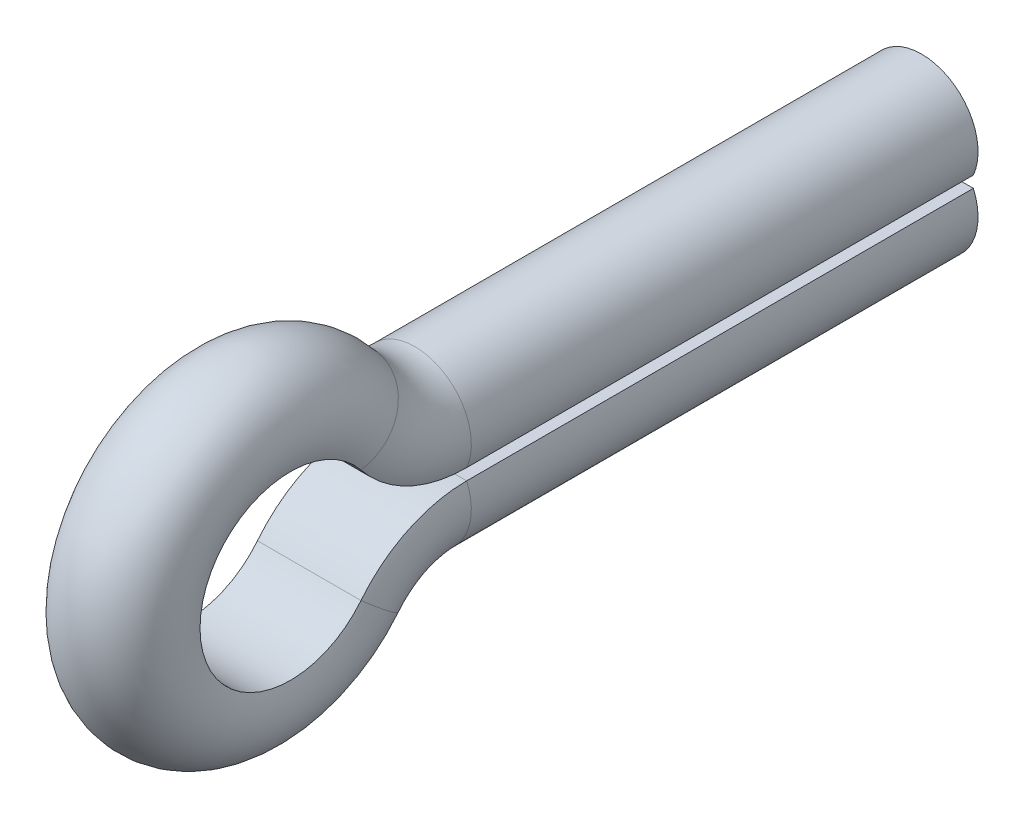
SolidWorks part; units mm, degrees
ref_plane "Front Plane" through (0, 0, 0) normal (0, 0, 1) x (1, 0, 0)
ref_plane "Top Plane" through (0, 0, 0) normal (0, 1, 0) x (1, 0, 0)
ref_plane "Right Plane" through (0, 0, 0) normal (1, 0, 0) x (0, 0, -1)
sketch "Sketch1" plane through (0, 0, 0) normal (1, 0, 0) x (0, 0, -1)
  line L0 (5, 0) -> (30.2482, 0) construction
  line L1 (7.8062, 1.25) -> (30.2482, 1.25)
  line L2 (7.8062, -1.25) -> (30.2482, -1.25)
  arc A0 (3.9031, 3.125) -> (3.9031, -3.125) centre (0, 0) ccw
  arc A1 (7.8062, -1.25) -> (3.9031, -3.125) centre (7.8062, -6.25) ccw
  arc A2 (3.9031, 3.125) -> (7.8062, 1.25) centre (7.8062, 6.25) ccw
  point P10 (4.8412, -1.25)
  point P13 (4.8412, 1.25)
  dimension "D1" = 10
  dimension "D3" = 5
  dimension "D2" = 2.5
ref_plane "Plane1" through (0, 0, -30.2482) normal (0, 0, 1) x (1, 0, 0)
sketch "Sketch5" plane through (0, 0, -30.2482) normal (0, 0, 1) x (1, 0, 0)
  line L2 (-2.2926, 0.2531) -> (2.2926, 0.2531)
  arc A0 (2.2926, 0.2531) -> (-2.2926, 0.2531) centre (0, 1.25) ccw
  point P8 (0, 0.2531)
  dimension "D1" = 5
sweep "Sweep1" add profiles "Sketch5" path "Sketch1"
